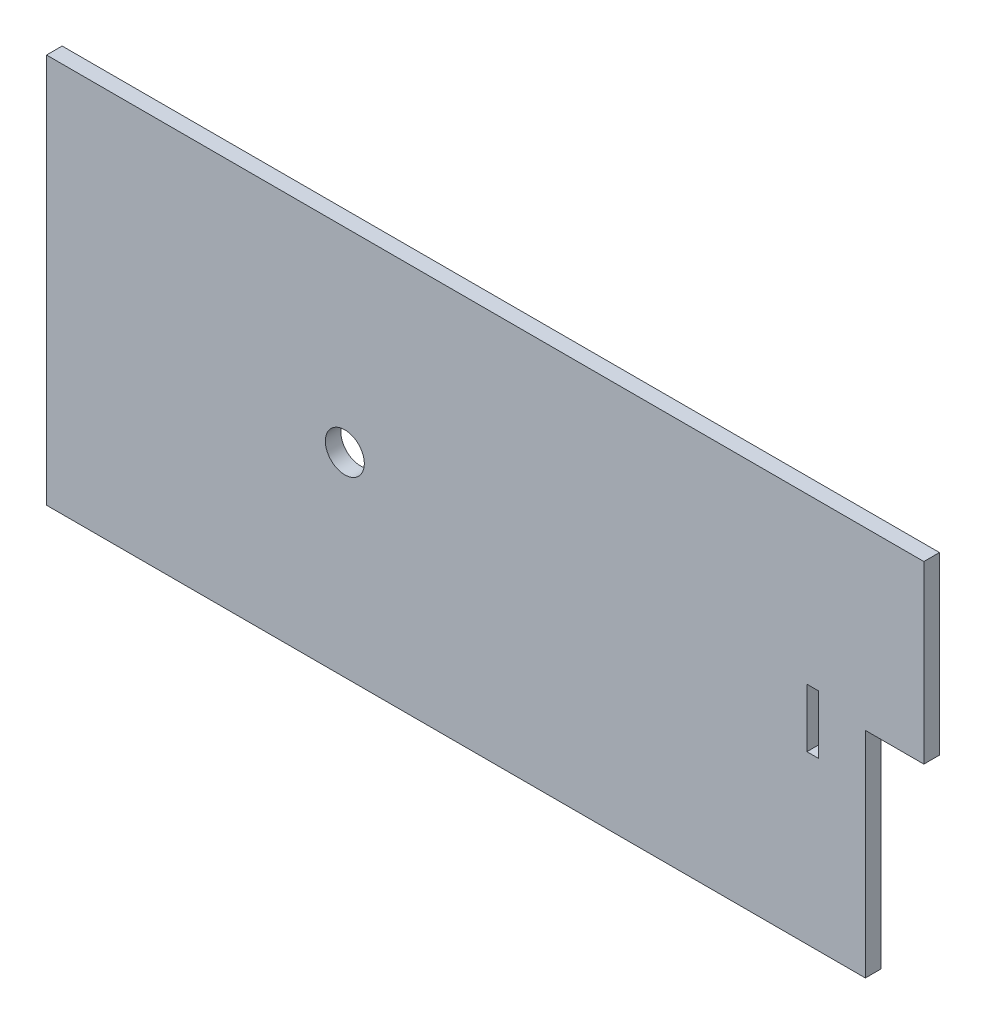
SolidWorks part; units mm, degrees
ref_plane "Front Plane" through (0, 0, 0) normal (0, 0, 1) x (1, 0, 0)
ref_plane "Top Plane" through (0, 0, 0) normal (0, 1, 0) x (1, 0, 0)
ref_plane "Right Plane" through (0, 0, 0) normal (1, 0, 0) x (0, 0, -1)
sketch "Sketch1" plane through (0, 0, 0) normal (0, 0, 1) x (1, 0, 0)
  line L0 (60, 50) -> (75, 50)
  line L1 (-150, -50) -> (60, -50)
  line L2 (-150, -50) -> (-150, 50)
  line L3 (-150, 50) -> (60, 50)
  line L4 (60, -50) -> (60, 50) construction
  line L5 (75, 50) -> (75, 5)
  line L6 (75, 5) -> (60, 5)
  line L7 (45, 7.7621) -> (48, 7.7621)
  line L8 (45, 7.7621) -> (45, -7.2379)
  line L9 (45, -7.2379) -> (48, -7.2379)
  line L10 (48, 7.7621) -> (48, -7.2379)
  line L11 (45, 7.7621) -> (48, -7.2379) construction
  line L12 (45, -7.2379) -> (48, 7.7621) construction
  line L13 (60, 5) -> (60, -50)
  circle A2 centre (-73.5, 0) radius 5
  point P1 (0, 0)
  point P8 (46.5, 0.2621)
  dimension "D3" = 45
  dimension "D4" = 15
  dimension "D5" = 3
  dimension "D1" = 150
  dimension "D2" = 100
  dimension "D6" = 15
  dimension "D7" = 45
  dimension "D8" = 73.5
  dimension "D9" = 60
extrude "Boss-Extrude1" add sketch "Sketch1" along normal blind 4
